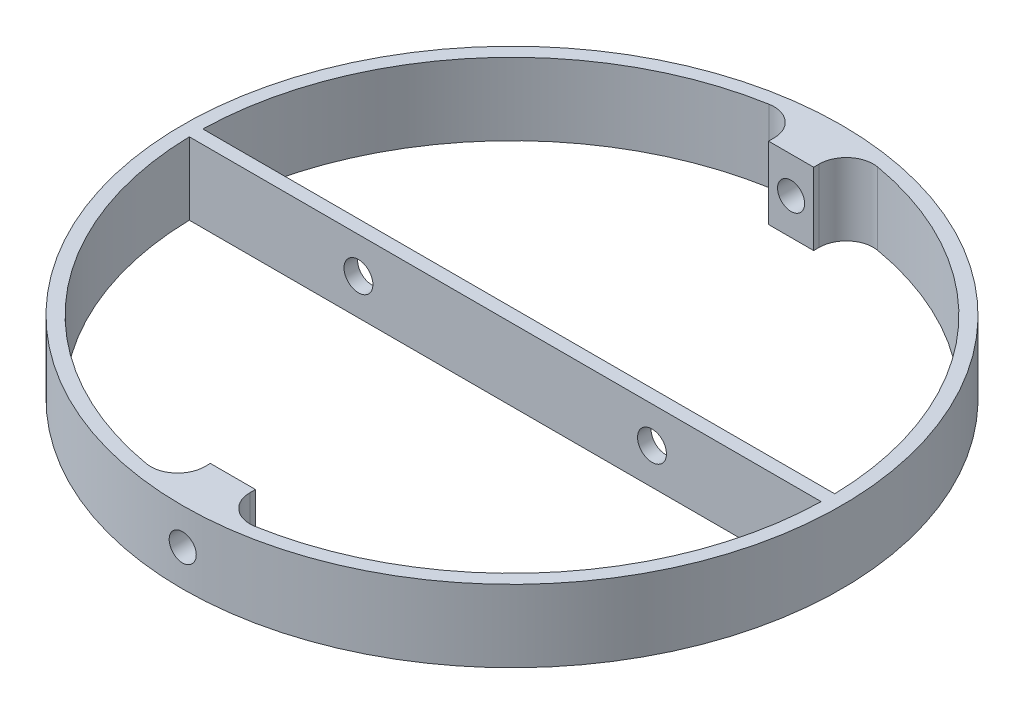
SolidWorks part; units mm, degrees
ref_plane "Plan de face" through (0, 0, 0) normal (0, 0, 1) x (1, 0, 0)
ref_plane "Plan de dessus" through (0, 0, 0) normal (0, 1, 0) x (1, 0, 0)
ref_plane "Plan de droite" through (0, 0, 0) normal (1, 0, 0) x (0, 0, -1)
sketch "Esquisse1" plane through (0, 0, 0) normal (0, 1, 0) x (1, 0, 0)
  line L0 (-34.992, 0.75) -> (34.992, 0.75)
  line L1 (-34.992, -0.75) -> (34.992, -0.75)
  line L2 (0, 0.75) -> (0, -0.75) construction
  line L3 (2.5, -34.9106) -> (2.5, -30.9106)
  line L4 (2.5, -30.9106) -> (-2.5, -30.9106)
  line L5 (-2.5, -30.9106) -> (-2.5, -34.9106)
  line L6 (2.5, 34.9106) -> (2.5, 30.9106)
  line L7 (2.5, 30.9106) -> (-2.5, 30.9106)
  line L8 (-2.5, 30.9106) -> (-2.5, 34.9106)
  circle A0 centre (0, 0) radius 35
  circle A1 centre (0, 0) radius 36.5
  point P13 (0, 0)
  point P18 (0, -30.9106)
  dimension "D1" = 73
  dimension "D2" = 1.5
  dimension "D3" = 1.5
  dimension "D4" = 4
  dimension "D5" = 5
extrude "Boss.-Extru.1" add sketch "Esquisse1" along normal mid plane 8 contours L0 L2 L1 A0 | A1 A0 | L2 L0 A0 L1 | L5 A0 L3 L4 | L6 A0 L8 L7
sketch "Esquisse2" plane through (0, 0, 0.75) normal (0, 0, 1) x (1, 0, 0)
  line L0 (-16.256, 0) -> (16.256, 0) construction
  circle A0 centre (-16.256, 0) radius 1.6
  circle A1 centre (16.256, 0) radius 1.6
  point P4 (0, 0)
  dimension "D1" = 32.512
  dimension "D2" = 3.2
ref_plane "Plan1" through (0, 0, 36.5) normal (0, 0, 1) x (1, 0, 0)
sketch "Esquisse3" plane through (0, 0, 36.5) normal (0, 0, 1) x (1, 0, 0)
  circle A0 centre (0, 0) radius 1.5
  dimension "D1" = 3
extrude "Enlèv. mat.-Extru.1" cut sketch "Esquisse3" against normal up to next
mirror "Symétrie1" about plane through (0, 0, 0) normal (0, 0, 1) of "Enlèv. mat.-Extru.1"
extrude "Enlèv. mat.-Extru.2" cut sketch "Esquisse2" against normal up to next
fillet "Congé1" radius 3 4 edges at (-2.5, 0, 34.9106) (2.5, 0, 34.9106) (2.5, 0, -34.9106) (-2.5, 0, -34.9106)
